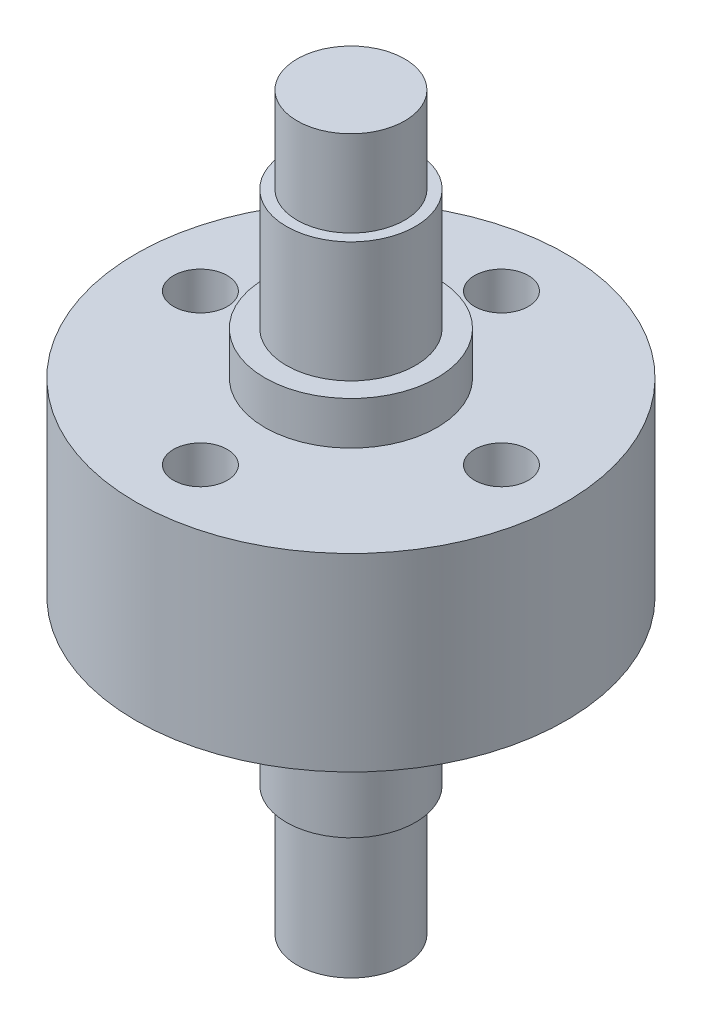
SolidWorks part; units mm, degrees
ref_plane "前视基准面" through (0, 0, 0) normal (0, 0, 1) x (1, 0, 0)
ref_plane "上视基准面" through (0, 0, 0) normal (0, 1, 0) x (1, 0, 0)
ref_plane "右视基准面" through (0, 0, 0) normal (1, 0, 0) x (0, 0, -1)
sketch "Model" plane through (0, 0, 0) normal (0, 0, 1) x (1, 0, 0)
  line L0 (-1.7864, 28.378) -> (-1.7864, -5.622)
  line L1 (8.2136, 7.978) -> (8.2136, 16.778)
  line L3 (2.2136, 16.778) -> (2.2136, 18.778)
  line L5 (2.2136, 5.978) -> (2.2136, 7.978)
  line L7 (1.2136, 0.378) -> (1.2136, 5.978)
  line L9 (1.2136, 18.778) -> (1.2136, 24.378)
  line L11 (0.7136, -5.622) -> (0.7136, 0.378)
  line L13 (0.7136, 24.378) -> (0.7136, 28.378)
  line L16 (1.2136, 18.778) -> (2.2136, 18.778)
  line L20 (-1.7864, -5.622) -> (0.7136, -5.622)
  line L21 (-1.7864, 28.378) -> (0.7136, 28.378)
  line L22 (-1.7864, 28.378) -> (-1.7864, -5.622) construction
  line L23 (0.7136, 24.378) -> (1.2136, 24.378)
  line L24 (2.2136, 16.778) -> (8.2136, 16.778)
  line L25 (2.2136, 7.978) -> (8.2136, 7.978)
  line L26 (1.2136, 5.978) -> (2.2136, 5.978)
  line L27 (0.7136, 0.378) -> (1.2136, 0.378)
revolve "旋转1" add sketch "Model" angle 360 about L22
sketch "草图2" plane through (0, 7.978, 0) normal (0, -1, 0) x (1, 0, 0)
  circle A0 centre (-1.7864, 0) radius 7 construction
  circle A1 centre (-1.7864, 7) radius 1.5
  dimension "D1" = 14
  dimension "D2" = 3
hole_wizard "M3 螺纹孔1" positions "3D草图1" profile "草图4" tap size "M3" standard "GB" end condition through all
sketch3d "3D草图1"
  point P0 (-1.7864, 7.978, 7)
sketch "草图4" plane through (-1.7864, 7.978, 7) normal (1, 0, 0) x (0, 0, -1)
  line L0 (0, 0) -> (0, 20.4)
  line L1 (0, 20.4) -> (1.25, 20.4)
  line L2 (1.25, 20.4) -> (1.25, 0)
  line L5 (1.25, 0) -> (0, 0)
  line L11 (0, -6.35) -> (0, 107.95) construction
  dimension "通孔螺纹孔钻头直径" = 2.5
  dimension "通孔螺纹孔钻头深度" = 20.4
cosmetic thread "孔螺蚊线1" parameters "D2"=3
pattern_circular "阵列(圆周)1" count 4 over 360 about axis through (-1.7864, 0, 0) along (0, 1, 0) of "M3 螺纹孔1"
